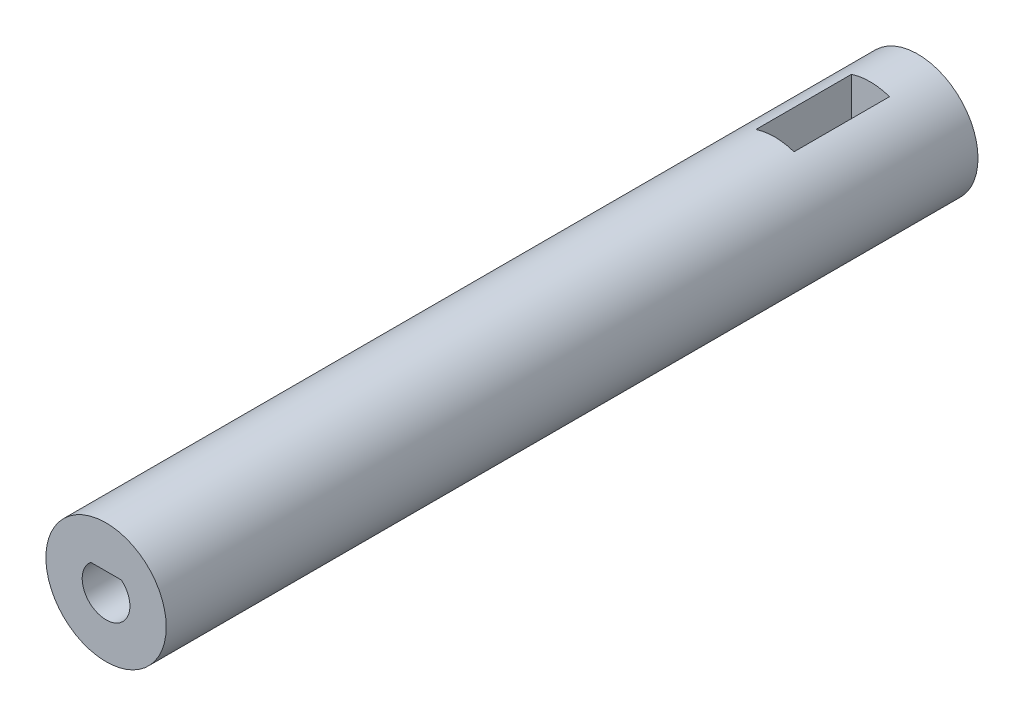
SolidWorks part; units mm, degrees
material "Alloy Steel"
ref_plane "Front Plane" through (0, 0, 0) normal (0, 0, 1) x (1, 0, 0)
ref_plane "Top Plane" through (0, 0, 0) normal (0, 1, 0) x (1, 0, 0)
ref_plane "Right Plane" through (0, 0, 0) normal (1, 0, 0) x (0, 0, -1)
sketch "Sketch1" plane through (0, 0, 0) normal (0, 0, 1) x (1, 0, 0)
  circle A0 centre (0, 0) radius 6.3
extrude "Boss-Extrude1" add sketch "Sketch1" along normal blind 80 and the other way blind 5
sketch "Sketch6" plane through (0, 0, 0) normal (0, 1, 0) x (1, 0, 0)
  line L0 (0, 0) -> (0, -70)
  line L8 (0, 0) -> (-1.9552, 0)
  line L11 (2.0384, -10) -> (-1.9552, -10)
  line L14 (-1.9552, 0) -> (-1.9552, -10)
  line L15 (0, 0) -> (2.0384, 0)
  line L16 (2.0384, 0) -> (2.0384, -10)
  dimension "D5" = 70
  dimension "D6" = 10
  dimension "D7" = 3.9935
extrude "Cut-Extrude1" cut sketch "Sketch6" along normal blind 10
sketch "Sketch7" plane through (0, 0, 80) normal (0, 0, 1) x (1, 0, 0)
  line L0 (0, 0) -> (0, 1.9153)
  line L1 (0, 1.9153) -> (1.6067, 1.9153)
  line L2 (0, 1.9153) -> (-1.6067, 1.9153)
  circle A0 centre (0, 0) radius 2.5
  dimension "D1" = 5
  dimension "D2" = 1.9153
extrude "Cut-Extrude3" cut sketch "Sketch7" against normal blind 17
